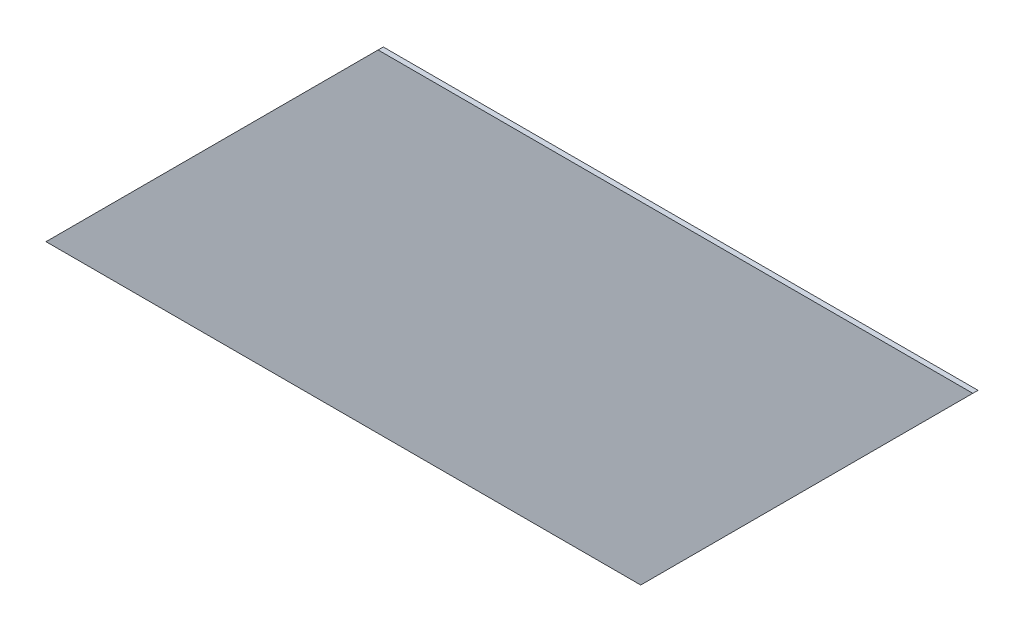
SolidWorks part; units mm, degrees
ref_plane "Front Plane" through (0, 0, 0) normal (0, 0, 1) x (1, 0, 0)
ref_plane "Top Plane" through (0, 0, 0) normal (0, 1, 0) x (1, 0, 0)
ref_plane "Right Plane" through (0, 0, 0) normal (1, 0, 0) x (0, 0, -1)
sketch "Sketch1" plane through (0, 0, 0) normal (0, 0, 1) x (1, 0, 0)
  line L0 (181.9529, -101.6) -> (385.1529, 101.6)
  line L1 (-181.9529, -101.6) -> (181.9529, -101.6)
  line L2 (-181.9529, -101.6) -> (-181.9529, 101.6) construction
  line L3 (-181.9529, 101.6) -> (21.2471, 101.6) construction
  line L4 (181.9529, -101.6) -> (181.9529, 101.6) construction
  line L5 (-181.9529, -101.6) -> (181.9529, 101.6) construction
  line L6 (-181.9529, 101.6) -> (181.9529, -101.6) construction
  line L7 (385.1529, 101.6) -> (181.9529, 101.6)
  line L8 (-181.9529, -101.6) -> (21.2471, 101.6)
  line L9 (21.2471, 101.6) -> (181.9529, 101.6)
  point P0 (0, 0)
  point P8 (64.6762, 101.6)
  dimension "D1" = 363.9058
  dimension "D2" = 203.2
  dimension "D3" = 45
  dimension "D4" = 45
extrude "Boss-Extrude1" add sketch "Sketch1" along normal blind 3.175
